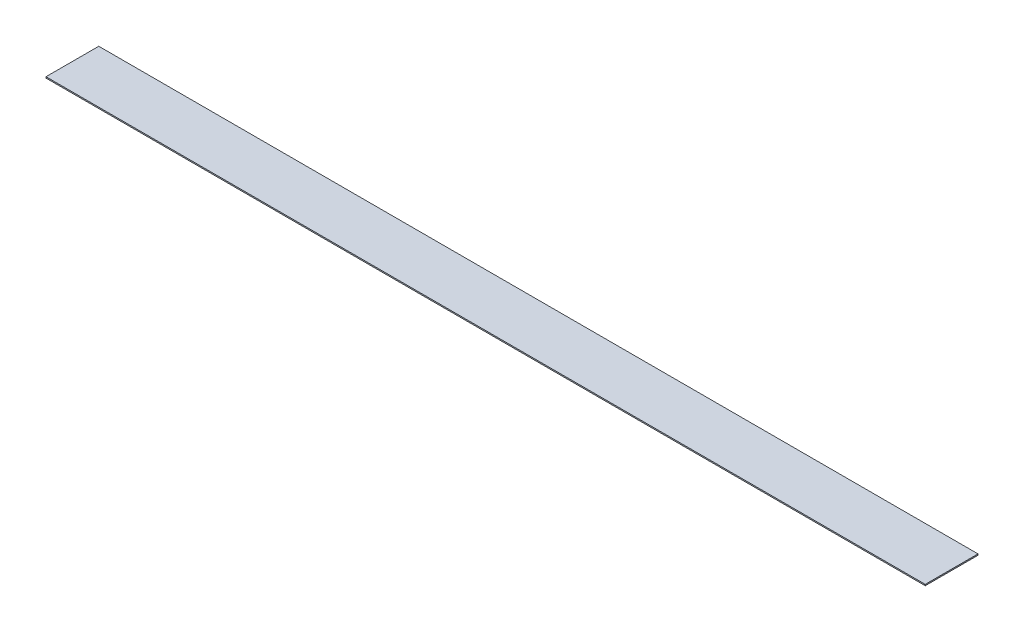
SolidWorks part; units mm, degrees
material "Copper"
ref_plane "Front Plane" through (0, 0, 0) normal (0, 0, 1) x (1, 0, 0)
ref_plane "Top Plane" through (0, 0, 0) normal (0, 1, 0) x (1, 0, 0)
ref_plane "Right Plane" through (0, 0, 0) normal (1, 0, 0) x (0, 0, -1)
sketch "Sketch1" plane through (0, 0, 0) normal (0, 1, 0) x (1, 0, 0)
  line L1 (-25, 1.5) -> (25, 1.5)
  line L2 (-25, 1.5) -> (-25, -1.5)
  line L3 (-25, -1.5) -> (25, -1.5)
  line L4 (25, 1.5) -> (25, -1.5)
  line L5 (-25, 1.5) -> (25, -1.5) construction
  line L6 (-25, -1.5) -> (25, 1.5) construction
  point P0 (0, 0)
  dimension "D1" = 50
  dimension "D2" = 3
extrude "Boss-Extrude1" add sketch "Sketch1" along normal blind 0.07
